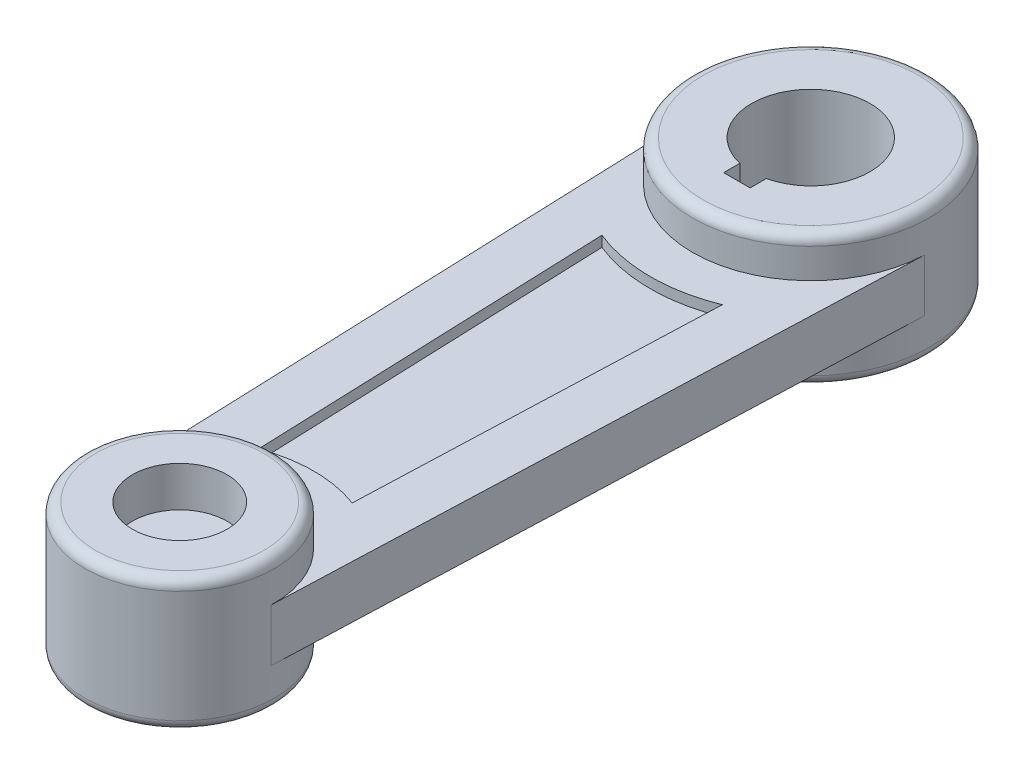
SolidWorks part; units mm, degrees
ref_plane "Front Plane" through (0, 0, 0) normal (0, 0, 1) x (1, 0, 0)
ref_plane "Top Plane" through (0, 0, 0) normal (0, 1, 0) x (1, 0, 0)
ref_plane "Right Plane" through (0, 0, 0) normal (1, 0, 0) x (0, 0, -1)
sketch "Sketch1" plane through (0, 0, 0) normal (0, 1, 0) x (1, 0, 0)
  circle A0 centre (0, 0) radius 45
  circle A1 centre (0, 0) radius 22.5
  circle A2 centre (0, 300) radius 56.25
  circle A3 centre (0, 300) radius 28.15
  dimension "D1" = 112.5
  dimension "D2" = 56.3
  dimension "D3" = 90
  dimension "D4" = 45
  dimension "D5" = 300
extrude "Boss-Extrude1" add sketch "Sketch1" along normal mid plane 63.3
sketch "Sketch2" plane through (0, 0, 0) normal (0, 1, 0) x (1, 0, 0)
  line L0 (56.2104, 297.8906) -> (44.9683, -1.6875)
  line L2 (-44.9683, -1.6875) -> (-56.2104, 297.8906)
  circle A0 centre (0, 0) radius 45 construction
  circle A1 centre (0, 300) radius 56.25 construction
  arc A2 (-44.9683, -1.6875) -> (44.9683, -1.6875) centre (0, 0) ccw
  arc A3 (56.2104, 297.8906) -> (-56.2104, 297.8906) centre (0, 300) ccw
extrude "Boss-Extrude2" add sketch "Sketch2" along normal mid plane 25
sketch "Sketch3" plane through (0, 12.5, 0) normal (0, 1, 0) x (1, 0, 0)
  line L9 (19.9859, -0.75) -> (31.228, 298.8281)
  line L10 (22.2559, 59.7389) -> (28.6198, 229.3249)
  line L12 (-31.228, 298.8281) -> (-19.9859, -0.75)
  line L13 (-28.6198, 229.3249) -> (-22.2559, 59.7389)
  arc A0 (-28.6198, 229.3249) -> (28.6198, 229.3249) centre (0, 300) ccw
  arc A1 (22.2559, 59.7389) -> (-22.2559, 59.7389) centre (0, 0) ccw
  dimension "D1" = 152.5
  dimension "D2" = 127.5
  dimension "D3" = 25
  dimension "D4" = 25
extrude "Cut-Extrude1" cut sketch "Sketch3" against normal blind 5
mirror "Mirror1" about plane through (0, 0, 0) normal (0, 1, 0) of "Cut-Extrude1"
sketch "Sketch4" plane through (0, 31.65, 0) normal (0, 1, 0) x (1, 0, 0)
  line L0 (0, 300) -> (0, 285.1672) construction
  line L2 (6.3, 272.564) -> (6.3, 264.864)
  line L3 (6.3, 264.864) -> (-6.3, 264.864)
  line L4 (-6.3, 272.564) -> (-6.3, 264.864)
  circle A0 centre (0, 300) radius 28.15 construction
  arc A1 (6.3, 272.564) -> (-6.3, 272.564) centre (0, 300) ccw
  dimension "D1" = 7.7
  dimension "D2" = 12.6
extrude "Cut-Extrude2" cut sketch "Sketch4" against normal through all
fillet "Fillet1" radius 5 4 edges at (0, 31.65, 45) (0, -31.65, 45) (0, -31.65, -243.75) (0, 31.65, -243.75)
